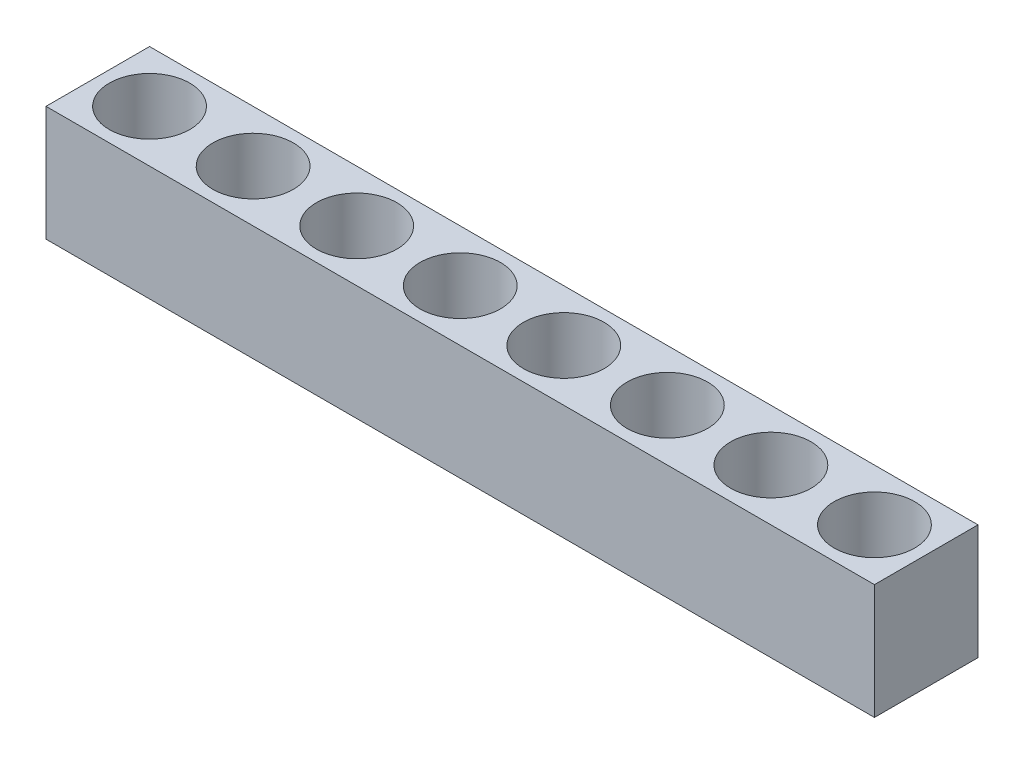
SolidWorks part; units mm, degrees
ref_plane "Front Plane" through (0, 0, 0) normal (0, 0, 1) x (1, 0, 0)
ref_plane "Top Plane" through (0, 0, 0) normal (0, 1, 0) x (1, 0, 0)
ref_plane "Right Plane" through (0, 0, 0) normal (1, 0, 0) x (0, 0, -1)
sketch "Sketch1" plane through (0, 0, 0) normal (0, 1, 0) x (1, 0, 0)
  line L0 (0, 0) -> (0, 22.2718) construction
  line L1 (-36, 4.5) -> (36, 4.5)
  line L2 (36, -4.5) -> (-36, -4.5)
  line L3 (-36, 4.5) -> (-36, -4.5)
  line L4 (36, -4.5) -> (36, 4.5)
  circle A0 centre (0, 0) radius 4.5 construction
  circle A1 centre (-4.5, 0) radius 3.5
  circle A2 centre (4.5, 0) radius 3.5
  circle A3 centre (13.5, 0) radius 3.5
  circle A4 centre (22.5, 0) radius 3.5
  circle A5 centre (31.5, 0) radius 3.5
  circle A6 centre (-13.5, 0) radius 3.5
  circle A7 centre (-22.5, 0) radius 3.5
  circle A8 centre (-31.5, 0) radius 3.5
  circle A9 centre (-31.5, 0) radius 4.5 construction
  circle A10 centre (31.5, 0) radius 4.5 construction
  dimension "D1" = 9
  dimension "D2" = 9
extrude "Boss-Extrude1" add sketch "Sketch1" against normal blind 10
